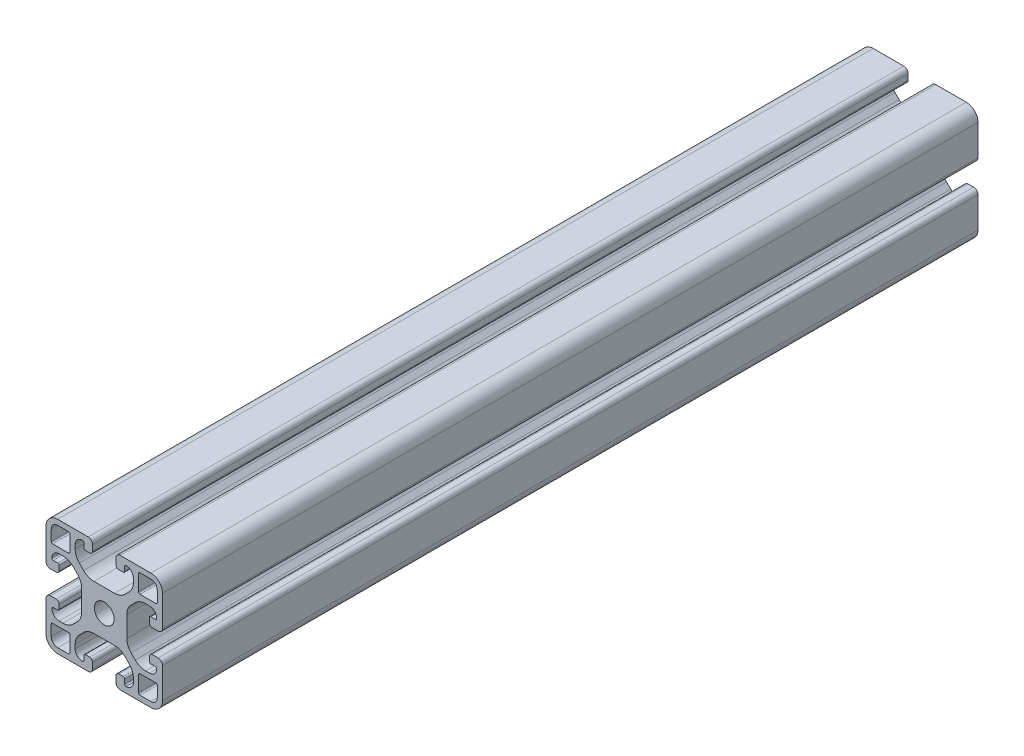
SolidWorks part; units mm, degrees
ref_plane "Plan de face" through (0, 0, 0) normal (0, 0, 1) x (1, 0, 0)
ref_plane "Plan de dessus" through (0, 0, 0) normal (0, 1, 0) x (1, 0, 0)
ref_plane "Plan de droite" through (0, 0, 0) normal (1, 0, 0) x (0, 0, -1)
ref_plane "Plan1" through (0, 0, -30) normal (0, 0, -1) x (-1, 0, 0)
sketch "Esquisse1" plane through (0, 0, -30) normal (0, 0, -1) x (-1, 0, 0)
  line L0 (-4.5, 15) -> (-4.5, 13.5)
  line L1 (-4, 13) -> (-2.5, 13)
  line L2 (-4.5, 10) -> (-5.8076, 10)
  line L3 (-9.3431, 11.4645) -> (-10.7855, 12.9069)
  line L4 (-12.25, 16.4424) -> (-12.25, 23.5576)
  line L5 (-10.7855, 27.0931) -> (-9.3431, 28.5355)
  line L6 (-5.8076, 30) -> (-4.5, 30)
  line L7 (-2.5, 27) -> (-4, 27)
  line L8 (-4.5, 26.5) -> (-4.5, 25)
  line L9 (-3.5, 24) -> (-1.5, 24)
  line L10 (0, 25.5) -> (0, 36)
  line L11 (-4, 40) -> (-14.5, 40)
  line L12 (-16, 38.5) -> (-16, 36.5)
  line L13 (-15, 35.5) -> (-13.5, 35.5)
  line L14 (-13, 36) -> (-13, 37.5)
  line L15 (-10, 35.5) -> (-10, 34.1924)
  line L16 (-11.4645, 30.6569) -> (-12.9069, 29.2145)
  line L17 (-16.4424, 27.75) -> (-23.5576, 27.75)
  line L18 (-27.0931, 29.2145) -> (-28.5355, 30.6569)
  line L19 (-30, 34.1924) -> (-30, 35.5)
  line L20 (-27, 37.5) -> (-27, 36)
  line L21 (-26.5, 35.5) -> (-25, 35.5)
  line L22 (-24, 36.5) -> (-24, 38.5)
  line L23 (-25.5, 40) -> (-36, 40)
  line L24 (-40, 36) -> (-40, 25.5)
  line L25 (-38.5, 24) -> (-36.5, 24)
  line L26 (-35.5, 25) -> (-35.5, 26.5)
  line L27 (-36, 27) -> (-37.5, 27)
  line L28 (-35.5, 30) -> (-34.1924, 30)
  line L29 (-30.6569, 28.5355) -> (-29.2145, 27.0931)
  line L30 (-27.75, 23.5576) -> (-27.75, 16.4424)
  line L31 (-29.2145, 12.9069) -> (-30.6569, 11.4645)
  line L32 (-34.1924, 10) -> (-35.5, 10)
  line L33 (-37.5, 13) -> (-36, 13)
  line L34 (-35.5, 13.5) -> (-35.5, 15)
  line L35 (-36.5, 16) -> (-38.5, 16)
  line L36 (-40, 14.5) -> (-40, 4)
  line L37 (-36, 0) -> (-25.5, 0)
  line L38 (-24, 1.5) -> (-24, 3.5)
  line L39 (-25, 4.5) -> (-26.5, 4.5)
  line L40 (-27, 4) -> (-27, 2.5)
  line L41 (-30, 4.5) -> (-30, 5.8076)
  line L42 (-28.5355, 9.3431) -> (-27.0931, 10.7855)
  line L43 (-23.5576, 12.25) -> (-16.4424, 12.25)
  line L44 (-12.9069, 10.7855) -> (-11.4645, 9.3431)
  line L45 (-10, 5.8076) -> (-10, 4.5)
  line L46 (-13, 2.5) -> (-13, 4)
  line L47 (-13.5, 4.5) -> (-15, 4.5)
  line L48 (-16, 3.5) -> (-16, 1.5)
  line L49 (-14.5, 0) -> (-4, 0)
  line L50 (0, 4) -> (0, 14.5)
  line L51 (-1.5, 16) -> (-3.5, 16)
  line L52 (-4, 1.8) -> (-7.7, 1.8)
  line L53 (-8.2, 2.3) -> (-8.2, 7.7)
  line L54 (-7.7, 8.2) -> (-2.3, 8.2)
  line L55 (-1.8, 7.7) -> (-1.8, 4)
  line L56 (-38.2, 4) -> (-38.2, 7.7)
  line L57 (-37.7, 8.2) -> (-32.3, 8.2)
  line L58 (-31.8, 7.7) -> (-31.8, 2.3)
  line L59 (-32.3, 1.8) -> (-36, 1.8)
  line L60 (-36, 38.2) -> (-32.3, 38.2)
  line L61 (-31.8, 37.7) -> (-31.8, 32.3)
  line L62 (-32.3, 31.8) -> (-37.7, 31.8)
  line L63 (-38.2, 32.3) -> (-38.2, 36)
  line L64 (-1.8, 36) -> (-1.8, 32.3)
  line L65 (-2.3, 31.8) -> (-7.7, 31.8)
  line L66 (-8.2, 32.3) -> (-8.2, 37.7)
  line L67 (-7.7, 38.2) -> (-4, 38.2)
  arc A0 (-4.5, 13.5) -> (-4, 13) centre (-4, 13.5) ccw
  arc A1 (-2.5, 13) -> (-2, 12.5) centre (-2.5, 12.5) cw
  arc A2 (-2, 12.5) -> (-4.5, 10) centre (-4.5, 12.5) cw
  arc A3 (-5.8076, 10) -> (-9.3431, 11.4645) centre (-5.8076, 15) cw
  arc A4 (-10.7855, 12.9069) -> (-12.25, 16.4424) centre (-7.25, 16.4424) cw
  arc A5 (-12.25, 23.5576) -> (-10.7855, 27.0931) centre (-7.25, 23.5576) cw
  arc A6 (-9.3431, 28.5355) -> (-5.8076, 30) centre (-5.8076, 25) cw
  arc A7 (-4.5, 30) -> (-2, 27.5) centre (-4.5, 27.5) cw
  arc A8 (-2, 27.5) -> (-2.5, 27) centre (-2.5, 27.5) cw
  arc A9 (-4, 27) -> (-4.5, 26.5) centre (-4, 26.5) ccw
  arc A10 (-4.5, 25) -> (-3.5, 24) centre (-3.5, 25) ccw
  arc A11 (-1.5, 24) -> (0, 25.5) centre (-1.5, 25.5) ccw
  arc A12 (0, 36) -> (-4, 40) centre (-4, 36) ccw
  arc A13 (-14.5, 40) -> (-16, 38.5) centre (-14.5, 38.5) ccw
  arc A14 (-16, 36.5) -> (-15, 35.5) centre (-15, 36.5) ccw
  arc A15 (-13.5, 35.5) -> (-13, 36) centre (-13.5, 36) ccw
  arc A16 (-13, 37.5) -> (-12.5, 38) centre (-12.5, 37.5) cw
  arc A17 (-12.5, 38) -> (-10, 35.5) centre (-12.5, 35.5) cw
  arc A18 (-10, 34.1924) -> (-11.4645, 30.6569) centre (-15, 34.1924) cw
  arc A19 (-12.9069, 29.2145) -> (-16.4424, 27.75) centre (-16.4424, 32.75) cw
  arc A20 (-23.5576, 27.75) -> (-27.0931, 29.2145) centre (-23.5576, 32.75) cw
  arc A21 (-28.5355, 30.6569) -> (-30, 34.1924) centre (-25, 34.1924) cw
  arc A22 (-30, 35.5) -> (-27.5, 38) centre (-27.5, 35.5) cw
  arc A23 (-27.5, 38) -> (-27, 37.5) centre (-27.5, 37.5) cw
  arc A24 (-27, 36) -> (-26.5, 35.5) centre (-26.5, 36) ccw
  arc A25 (-25, 35.5) -> (-24, 36.5) centre (-25, 36.5) ccw
  arc A26 (-24, 38.5) -> (-25.5, 40) centre (-25.5, 38.5) ccw
  arc A27 (-36, 40) -> (-40, 36) centre (-36, 36) ccw
  arc A28 (-40, 25.5) -> (-38.5, 24) centre (-38.5, 25.5) ccw
  arc A29 (-36.5, 24) -> (-35.5, 25) centre (-36.5, 25) ccw
  arc A30 (-35.5, 26.5) -> (-36, 27) centre (-36, 26.5) ccw
  arc A31 (-37.5, 27) -> (-38, 27.5) centre (-37.5, 27.5) cw
  arc A32 (-38, 27.5) -> (-35.5, 30) centre (-35.5, 27.5) cw
  arc A33 (-34.1924, 30) -> (-30.6569, 28.5355) centre (-34.1924, 25) cw
  arc A34 (-29.2145, 27.0931) -> (-27.75, 23.5576) centre (-32.75, 23.5576) cw
  arc A35 (-27.75, 16.4424) -> (-29.2145, 12.9069) centre (-32.75, 16.4424) cw
  arc A36 (-30.6569, 11.4645) -> (-34.1924, 10) centre (-34.1924, 15) cw
  arc A37 (-35.5, 10) -> (-38, 12.5) centre (-35.5, 12.5) cw
  arc A38 (-38, 12.5) -> (-37.5, 13) centre (-37.5, 12.5) cw
  arc A39 (-36, 13) -> (-35.5, 13.5) centre (-36, 13.5) ccw
  arc A40 (-35.5, 15) -> (-36.5, 16) centre (-36.5, 15) ccw
  arc A41 (-38.5, 16) -> (-40, 14.5) centre (-38.5, 14.5) ccw
  arc A42 (-40, 4) -> (-36, 0) centre (-36, 4) ccw
  arc A43 (-25.5, 0) -> (-24, 1.5) centre (-25.5, 1.5) ccw
  arc A44 (-24, 3.5) -> (-25, 4.5) centre (-25, 3.5) ccw
  arc A45 (-26.5, 4.5) -> (-27, 4) centre (-26.5, 4) ccw
  arc A46 (-27, 2.5) -> (-27.5, 2) centre (-27.5, 2.5) cw
  arc A47 (-27.5, 2) -> (-30, 4.5) centre (-27.5, 4.5) cw
  arc A48 (-30, 5.8076) -> (-28.5355, 9.3431) centre (-25, 5.8076) cw
  arc A49 (-27.0931, 10.7855) -> (-23.5576, 12.25) centre (-23.5576, 7.25) cw
  arc A50 (-16.4424, 12.25) -> (-12.9069, 10.7855) centre (-16.4424, 7.25) cw
  arc A51 (-11.4645, 9.3431) -> (-10, 5.8076) centre (-15, 5.8076) cw
  arc A52 (-10, 4.5) -> (-12.5, 2) centre (-12.5, 4.5) cw
  arc A53 (-12.5, 2) -> (-13, 2.5) centre (-12.5, 2.5) cw
  arc A54 (-13, 4) -> (-13.5, 4.5) centre (-13.5, 4) ccw
  arc A55 (-15, 4.5) -> (-16, 3.5) centre (-15, 3.5) ccw
  arc A56 (-16, 1.5) -> (-14.5, 0) centre (-14.5, 1.5) ccw
  arc A57 (-4, 0) -> (0, 4) centre (-4, 4) ccw
  arc A58 (0, 14.5) -> (-1.5, 16) centre (-1.5, 14.5) ccw
  arc A59 (-3.5, 16) -> (-4.5, 15) centre (-3.5, 15) ccw
  circle A60 centre (-20, 20) radius 3.4
  arc A61 (-1.8, 4) -> (-4, 1.8) centre (-4, 4) cw
  arc A62 (-7.7, 1.8) -> (-8.2, 2.3) centre (-7.7, 2.3) cw
  arc A63 (-8.2, 7.7) -> (-7.7, 8.2) centre (-7.7, 7.7) cw
  arc A64 (-2.3, 8.2) -> (-1.8, 7.7) centre (-2.3, 7.7) cw
  arc A65 (-36, 1.8) -> (-38.2, 4) centre (-36, 4) cw
  arc A66 (-38.2, 7.7) -> (-37.7, 8.2) centre (-37.7, 7.7) cw
  arc A67 (-32.3, 8.2) -> (-31.8, 7.7) centre (-32.3, 7.7) cw
  arc A68 (-31.8, 2.3) -> (-32.3, 1.8) centre (-32.3, 2.3) cw
  arc A69 (-38.2, 36) -> (-36, 38.2) centre (-36, 36) cw
  arc A70 (-32.3, 38.2) -> (-31.8, 37.7) centre (-32.3, 37.7) cw
  arc A71 (-31.8, 32.3) -> (-32.3, 31.8) centre (-32.3, 32.3) cw
  arc A72 (-37.7, 31.8) -> (-38.2, 32.3) centre (-37.7, 32.3) cw
  arc A73 (-4, 38.2) -> (-1.8, 36) centre (-4, 36) cw
  arc A74 (-1.8, 32.3) -> (-2.3, 31.8) centre (-2.3, 32.3) cw
  arc A75 (-7.7, 31.8) -> (-8.2, 32.3) centre (-7.7, 32.3) cw
  arc A76 (-8.2, 37.7) -> (-7.7, 38.2) centre (-7.7, 37.7) cw
extrude "Boss.-Extru.1" add sketch "Esquisse1" against normal blind 280
